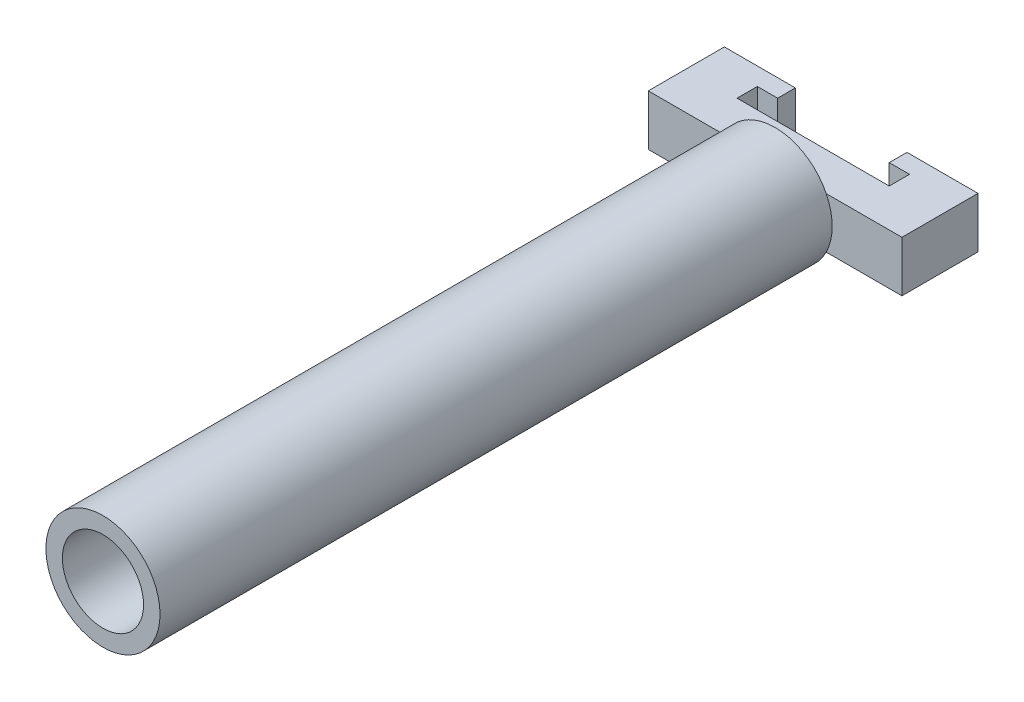
SolidWorks part; units mm, degrees
material "ABS"
ref_plane "Front Plane" through (0, 0, 0) normal (0, 0, 1) x (1, 0, 0)
ref_plane "Top Plane" through (0, 0, 0) normal (0, 1, 0) x (1, 0, 0)
ref_plane "Right Plane" through (0, 0, 0) normal (1, 0, 0) x (0, 0, -1)
sketch "Sketch1" plane through (0, 0, 0) normal (0, 0, 1) x (1, 0, 0)
  circle A0 centre (0, 0) radius 1.6
  circle A1 centre (0, 0) radius 2.25
  dimension "D1" = 3.2
  dimension "D2" = 4.5
extrude "Boss-Extrude1" add sketch "Sketch1" against normal blind 25
sketch "Sketch2" plane through (0, 0, -25) normal (0, 0, -1) x (-1, 0, 0)
  circle A0 centre (0, 0) radius 2.25
extrude "Boss-Extrude2" add sketch "Sketch2" along normal blind 1.5
sketch "Sketch3" plane through (0, 0, -26.5) normal (0, 0, -1) x (-1, 0, 0)
  line L1 (5, -1) -> (-5, -1)
  line L2 (5, -1) -> (5, 1)
  line L3 (5, 1) -> (-5, 1)
  line L4 (-5, -1) -> (-5, 1)
  line L5 (5, -1) -> (-5, 1) construction
  line L6 (5, 1) -> (-5, -1) construction
  point P0 (0, 0)
  dimension "D1" = 2
  dimension "D2" = 10
extrude "Boss-Extrude3" add sketch "Sketch3" along normal blind 1.5 contours L3 L4 L1 L2
sketch "Sketch4" plane through (0, 0, -28) normal (0, 0, -1) x (-1, 0, 0)
  line L0 (5, -1) -> (-5, -1) construction
  line L1 (-5, 1) -> (-3, 1)
  line L2 (-5, 1) -> (-5, -1)
  line L3 (-5, -1) -> (-3, -1)
  line L4 (-3, 1) -> (-3, -1)
  line L6 (5, 1) -> (3, 1)
  line L7 (5, 1) -> (5, -1)
  line L8 (5, -1) -> (3, -1)
  line L9 (3, 1) -> (3, -1)
  dimension "D1" = 2
  dimension "D2" = 2
extrude "Boss-Extrude4" add sketch "Sketch4" along normal blind 0.8
sketch "Sketch5" plane through (0, 0, -28.8) normal (0, 0, -1) x (-1, 0, 0)
  line L0 (3, -1) -> (-3, -1) construction
  line L1 (-5, 1) -> (-2.2, 1)
  line L2 (-5, 1) -> (-5, -1)
  line L3 (-5, -1) -> (-2.2, -1)
  line L4 (-2.2, 1) -> (-2.2, -1)
  line L5 (0, 0) -> (0, -5.02) construction
  line L6 (2.2, 1) -> (2.2, -1)
  line L7 (5, -1) -> (2.2, -1)
  line L8 (5, 1) -> (5, -1)
  line L9 (5, 1) -> (2.2, 1)
  dimension "D1" = 2.8
extrude "Boss-Extrude5" add sketch "Sketch5" along normal blind 0.7
